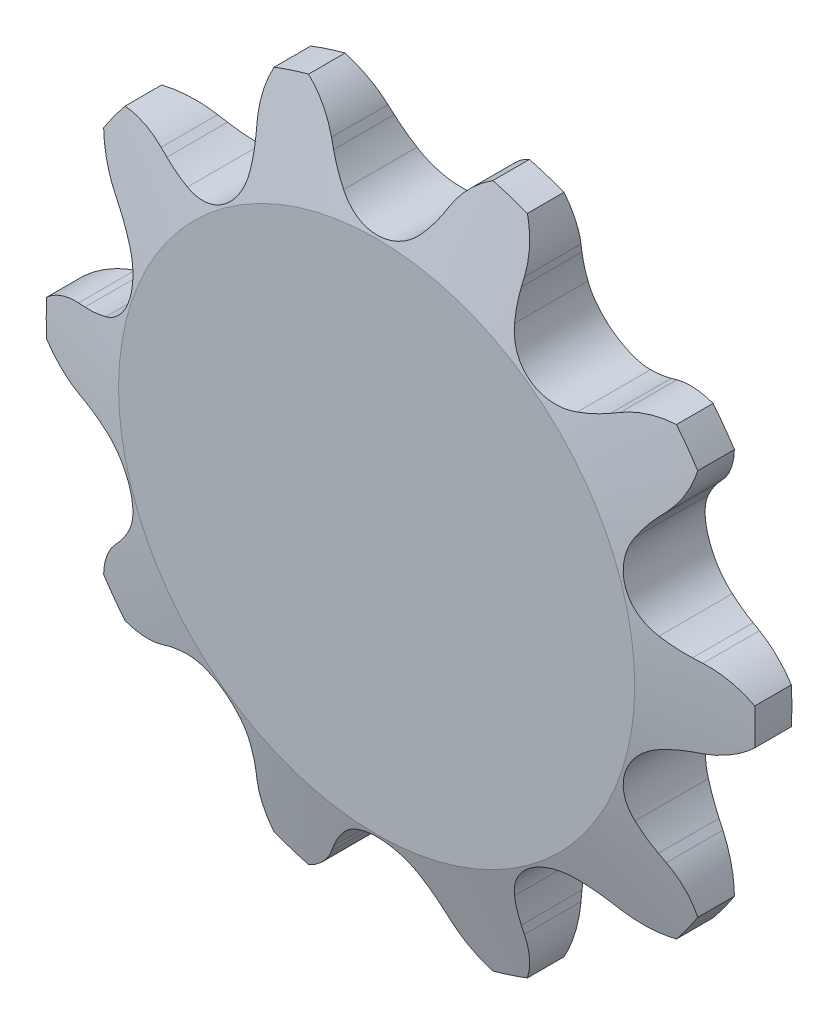
SolidWorks part; units mm, degrees
ref_plane "Front Plane" through (0, 0, 0) normal (0, 0, 1) x (1, 0, 0)
ref_plane "Top Plane" through (0, 0, 0) normal (0, 1, 0) x (1, 0, 0)
ref_plane "Right Plane" through (0, 0, 0) normal (1, 0, 0) x (0, 0, -1)
sketch "Chain Data" plane through (0, 0, 0) normal (0, 0, 1) x (1, 0, 0)
  line L0 (-518.2469, 244.3179) -> (-28.9136, 244.3179) construction
  text T0 "Source: https://isccompanies.com/wp-content/uploads/2016/03/ANSI-Roller-Chain-Sizes-Chart-734x661.jpg"
ref_axis "Centaur" through (0, 0, -87.4025) along (0, 0, 1)
sketch "Profile Master" plane through (0, 0, 0) normal (0, 0, 1) x (1, 0, 0)
  line L0 (0, 0) -> (0, 39.9687) construction
  line L1 (24.02, 10.2745) -> (-24.02, 10.2745) construction
  line L2 (-24.02, 12.0076) -> (24.02, 12.0076) construction
  line L3 (1.9936, 0) -> (1.9936, 39.9687) construction
  line L4 (1.9936, 12.0076) -> (-1.6608, 8.8308) construction
  line L5 (1.9936, 12.0076) -> (-1.8159, 9.9305) construction
  line L6 (-1.8159, 9.9305) -> (-2.8589, 11.8435) construction
  line L7 (-4.3965, 0) -> (-4.3965, 39.9687) construction
  line L8 (-24.02, 8.846) -> (24.02, 8.846) construction
  line L9 (0, 0) -> (-12.459, 38.3449) construction
  circle A0 centre (0, 0) radius 10.2745
  circle A1 centre (0, 10.2745) radius 1.6899
  arc A2 (-1.2754, 9.1658) -> (-1.8159, 9.9305) centre (1.977, 12.0379) cw
  circle A3 centre (-4.3965, 8.846) radius 2.7849
  point P7 (0, 10.2745)
  point P13 (-1.2754, 9.1658)
  point P17 (1.9936, 12.0076)
  point P22 (-3.7548, 11.556)
  point P27 (-4.3965, 8.846)
  dimension "D8" = 4.339
  dimension "D4" = 1.9936
  dimension "D10" = 1.4285
  dimension "D12" = 18
sketch "Tooth Profile" plane through (0, 0, 0) normal (0, 0, 1) x (1, 0, 0)
  line L0 (-1.8159, 9.9305) -> (-2.8589, 11.8435) construction
  line L1 (-1.8159, 9.9305) -> (-1.9514, 10.1791)
  line L2 (0, 0) -> (0, 39.9687) construction
  line L3 (0, 0) -> (0, 39.9687) construction
  line L4 (1.8159, 9.9305) -> (1.9514, 10.1791)
  circle A0 centre (0, 10.2745) radius 1.6899 construction
  arc A1 (-1.8159, 9.9305) -> (-1.2754, 9.1658) centre (1.977, 12.0379) ccw construction
  circle A2 centre (-4.3965, 8.846) radius 2.7849 construction
  arc A3 (-1.2754, 9.1658) -> (1.2754, 9.1658) centre (0, 10.2745) ccw
  arc A4 (-1.8159, 9.9305) -> (-1.2754, 9.1658) centre (1.977, 12.0379) ccw
  arc A5 (-1.9514, 10.1791) -> (-3.7548, 11.556) centre (-4.3965, 8.846) ccw
  arc A6 (1.9514, 10.1791) -> (3.7548, 11.556) centre (4.3965, 8.846) cw
  arc A7 (1.8159, 9.9305) -> (1.2754, 9.1658) centre (-1.977, 12.0379) cw
  arc A8 (3.7548, 11.556) -> (-3.7548, 11.556) centre (0, 0) ccw
  point P19 (-3.7548, 11.556)
sketch "OD Sketch" plane through (0, 0, 0) normal (0, 0, 1) x (1, 0, 0)
  line L0 (0, 10.2745) -> (-6.0392, 8.3123) construction
  line L1 (-3.0196, 9.2934) -> (-3.6083, 11.1051) construction
  arc A0 (-1.2754, 9.1658) -> (1.2754, 9.1658) centre (0, 10.2745) ccw construction
  circle A1 centre (0, 0) radius 10.2745 construction
  circle A2 centre (0, 0) radius 11.6766
  point P0 (0, 10.2745)
  dimension "D1" = 6.35
  dimension "D2" = 1.905
sketch "Sketch7" plane through (0, 0, 0) normal (1, 0, 0) x (0, 0, -1)
  line L0 (0, 11.6766) -> (0, -11.6766) construction
  line L1 (-1.397, 0) -> (1.397, 0)
  line L2 (-1.397, 0) -> (-1.397, 8.5016)
  line L3 (-1.397, 8.5016) -> (1.397, 8.5016) construction
  line L4 (1.397, 0) -> (1.397, 8.5016)
  line L5 (-1.397, 8.5016) -> (1.397, 8.5016) construction
  line L6 (-1.397, 8.5016) -> (-1.397, 11.6766) construction
  line L7 (-1.397, 11.6766) -> (1.397, 11.6766) construction
  line L8 (1.397, 8.5016) -> (1.397, 11.6766) construction
  line L9 (0, 11.6766) -> (0, -11.6766) construction
  line L10 (0.6033, 11.6766) -> (-0.6033, 11.6766)
  line L11 (-0.6033, 11.6766) -> (-1.397, 8.5016)
  line L12 (0.6033, 11.6766) -> (1.397, 8.5016)
  point P1 (0, 11.6766)
  point P4 (0, 0)
  point P16 (0, 11.6766)
  dimension "D1" = 2.794
  dimension "D2" = 3.175
  dimension "D3" = 0.7937
revolve "Revolve1" add sketch "Sketch7" angle 360 about axis through (0, 0, -87.4025) along (0, 0, 1)
extrude "Cut-Extrude1" cut sketch "Tooth Profile" along normal through all both and the other way through all
pattern_circular "CirPattern3" count 10 over 360 about axis through (0, 0, 0) along (0, 0, 1) of "Cut-Extrude1"
sketch "Pitch Diamiter" plane through (0, 0, 0) normal (0, 0, 1) x (1, 0, 0)
  circle A0 centre (0, 0) radius 10.2745
  dimension "D1" = 20.549
equation "\"D1@Profile Master\" = \"PD\""
equation "\"ChainNo\"= 25'Can only be 25 or 35"
equation "\"N\"= 10'# Of teeth"
equation "\"P\"= IIF ( \"ChainNo\" = 25 , 0.25 , IIF ( \"ChainNo\" = 35 , 0.375 , 0.25 ) )'Change to be not only 25 chain"
equation "\"PD\"= ( \"P\" ) / sin ( 180 / \"N\" )'Sprocket Pitch Diamiter"
equation "\"Dr\"= IIF ( \"ChainNo\" = 25 , 0.13 , IIF ( \"ChainNo\" = 35 , 0.2 , 0.13 ) )'Roller Diamiter"
equation "\"Ds\"= ( 1.0005 * \"Dr\" ) + .003"
equation "\"R\"= \"Ds\" / 2"
equation "\"D2@Profile Master\" = \"Ds\""
equation "\"M\"= ( .8 * \"Dr\" ) * ( cos ( 35 + ( 60 / \"N\" ) ) )"
equation "\"T\"= ( .8 * \"Dr\" ) * ( sin ( 35 + ( 60 / \"N\" ) ) )"
equation "\"D3@Profile Master\" = \"T\""
equation "\"D4@Profile Master\" = \"M\""
equation "\"A\"= 35 + ( 60 / \"N\" )"
equation "\"B\"= 18 - ( 56 / \"N\" )"
equation "\"E\"= ( 1.3025 * \"Dr\" ) + 0.0015"
equation "\"D5@Profile Master\" = \"A\""
equation "\"D6@Profile Master\" = \"E\""
equation "\"D7@Profile Master\" = \"B\""
equation "\"D8@Profile Master\" = \"E\""
equation "\"W\"= ( 1.4 * \"Dr\" ) * cos ( 180 / \"N\" )"
equation "\"V\"= ( 1.4 * \"Dr\" ) * sin ( 180 / \"N\" )"
equation "\"D9@Profile Master\" = \"W\""
equation "\"D10@Profile Master\" = \"V\""
equation "\"F\"= \"Dr\" * ( .8 * cos ( 18 - ( 56 / \"N\" ) ) + 1.4 * cos ( 17 - ( 64 / \"N\" ) ) - 1.3025 ) - .0015"
equation "\"D11@Profile Master\" = \"F\""
equation "\"D12@Profile Master\" = 180 / \"N\""
equation "\"D1@CirPattern3\"=\"N\""
equation "\"Thick\"= IIF ( \"ChainNo\" = 25 , 0.11 , IIF ( \"ChainNo\" = 35 , 0.168 , 0.11 ) )'Sprocket Thickness"
equation "\"D1@OD Sketch\" = \"P\""
equation "\"D2@OD Sketch\" = \"P\" * .3"
equation "\"D1@Sketch7\"=\"Thick\""
equation "\"D2@Sketch7\"=\"P\"/2"
equation "\"D3@Sketch7\"=\"P\"/8"
equation "\"D1@Pitch Diamiter\" = \"PD\""
